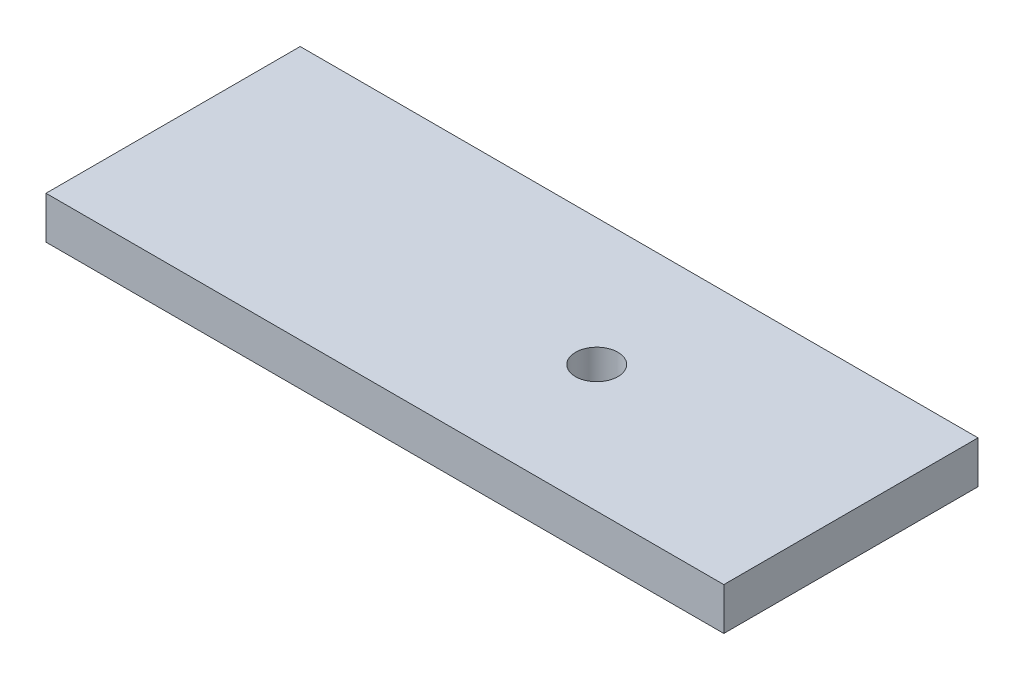
SolidWorks part; units mm, degrees
ref_plane "Front Plane" through (0, 0, 0) normal (0, 0, 1) x (1, 0, 0)
ref_plane "Top Plane" through (0, 0, 0) normal (0, 1, 0) x (1, 0, 0)
ref_plane "Right Plane" through (0, 0, 0) normal (1, 0, 0) x (0, 0, -1)
sketch "Sketch1" plane through (0, 0, 0) normal (0, 1, 0) x (1, 0, 0)
  line L0 (0, 9.525) -> (50.8, 9.525) construction
  line L1 (0, 0) -> (50.8, 0)
  line L2 (0, 0) -> (0, 19.05)
  line L3 (0, 19.05) -> (50.8, 19.05)
  line L4 (50.8, 0) -> (50.8, 19.05)
  dimension "D1" = 50.8
  dimension "D2" = 19.05
extrude "Boss-Extrude1" add sketch "Sketch1" along normal blind 3.175
sketch "Sketch2" plane through (0, 0, 0) normal (-1, 0, 0) x (0, 0, 1)
  line L0 (-19.05, 1.5875) -> (0, 1.5875) construction
  line L1 (-19.05, 3.175) -> (-19.05, 0) construction
  line L2 (0, 3.175) -> (0, 0) construction
  line L3 (-9.525, 3.175) -> (-9.525, 0) construction
  line L4 (-19.05, 3.175) -> (0, 3.175) construction
  line L5 (-19.05, 0) -> (0, 0) construction
  circle A0 centre (-5.08, 1.5875) radius 1.1906
  circle A1 centre (-13.97, 1.5875) radius 1.1906
  dimension "D1" = 2.3813
  dimension "D2" = 4.445
extrude "Cut-Extrude1" cut sketch "Sketch2" against normal blind 9.525
sketch "Sketch3" plane through (0, 3.175, 0) normal (0, 1, 0) x (1, 0, 0)
  line L0 (50.8, 9.525) -> (0, 9.525) construction
  line L1 (50.8, 0) -> (50.8, 19.05) construction
  line L2 (0, 19.05) -> (0, 0) construction
  circle A0 centre (31.75, 9.525) radius 1.5875
  dimension "D1" = 3.175
  dimension "D2" = 31.75
extrude "Cut-Extrude2" cut sketch "Sketch3" against normal through all
